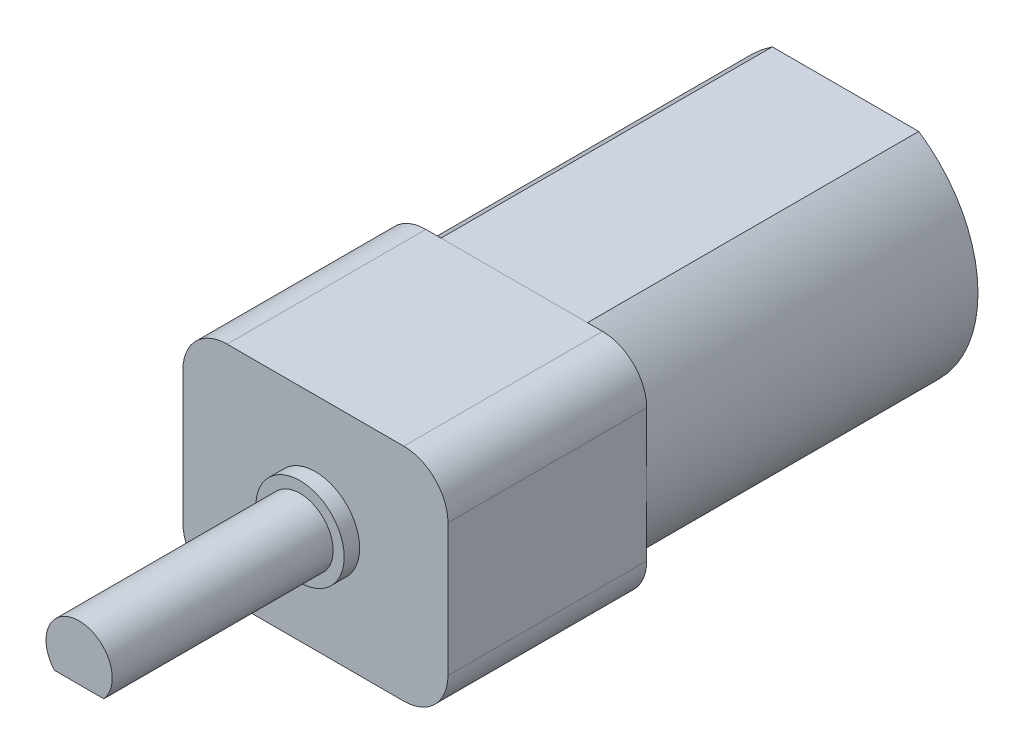
SolidWorks part; units mm, degrees
ref_plane "Front Plane" through (0, 0, 0) normal (0, 0, 1) x (1, 0, 0)
ref_plane "Top Plane" through (0, 0, 0) normal (0, 1, 0) x (1, 0, 0)
ref_plane "Right Plane" through (0, 0, 0) normal (1, 0, 0) x (0, 0, -1)
sketch "Sketch9" plane through (0, 0, 0) normal (0, 0, 1) x (1, 0, 0)
  line L5 (-6, -5) -> (6, 5) construction
  line L6 (-6, 5) -> (6, -5) construction
  line L13 (-3.3166, 5) -> (3.3166, 5)
  line L14 (-3.3166, -5) -> (3.3166, -5)
  arc A0 (-3.3166, 5) -> (-3.3166, -5) centre (0, 0) ccw
  arc A1 (3.3166, -5) -> (3.3166, 5) centre (0, 0) ccw
  dimension "D1" = 6
  dimension "D2" = 10
extrude "Мотор" add sketch "Sketch9" along normal blind 15 separate body contours A0 L14 A1 L13
sketch "Sketch2" plane through (0, 0, 0) normal (0, 0, -1) x (-1, 0, 0)
  circle A0 centre (0, 0) radius 2.5
extrude "Пятка мотора" add sketch "Sketch2" along normal blind 1.2
sketch "Sketch5" plane through (0, 0, 15) normal (0, 0, 1) x (1, 0, 0)
  line L1 (-6, -5) -> (6, -5)
  line L2 (-6, -5) -> (-6, 5)
  line L3 (-6, 5) -> (6, 5)
  line L4 (6, -5) -> (6, 5)
  line L5 (-6, -5) -> (6, 5) construction
  line L6 (-6, 5) -> (6, -5) construction
  point P0 (0, 0)
  dimension "D1" = 12
  dimension "D2" = 10
extrude "Редуктор" add sketch "Sketch5" along normal blind 9 separate body
fillet "Скругления редуктора" radius 2 4 edges at (-6, -5, 19.5) (6, -5, 19.5) (-6, 5, 19.5) (6, 5, 19.5)
sketch "Sketch6" plane through (0, 0, 24) normal (0, 0, 1) x (1, 0, 0)
  circle A0 centre (0, 0) radius 2
extrude "Опора вала" add sketch "Sketch6" along normal blind 0.7
sketch "Sketch7" plane through (0, 0, 24.7) normal (0, 0, 1) x (1, 0, 0)
  circle A0 centre (0, 0) radius 1.5
extrude "Вал" add sketch "Sketch7" along normal blind 10
sketch "Sketch8" plane through (0, 0, 34.7) normal (0, 0, 1) x (1, 0, 0)
  line L0 (-1.118, -1) -> (1.118, -1)
  arc A0 (-1.118, -1) -> (1.118, -1) centre (0, 0) ccw
  dimension "D1" = 1
extrude "Лыска вала" cut sketch "Sketch8" against normal blind 10
